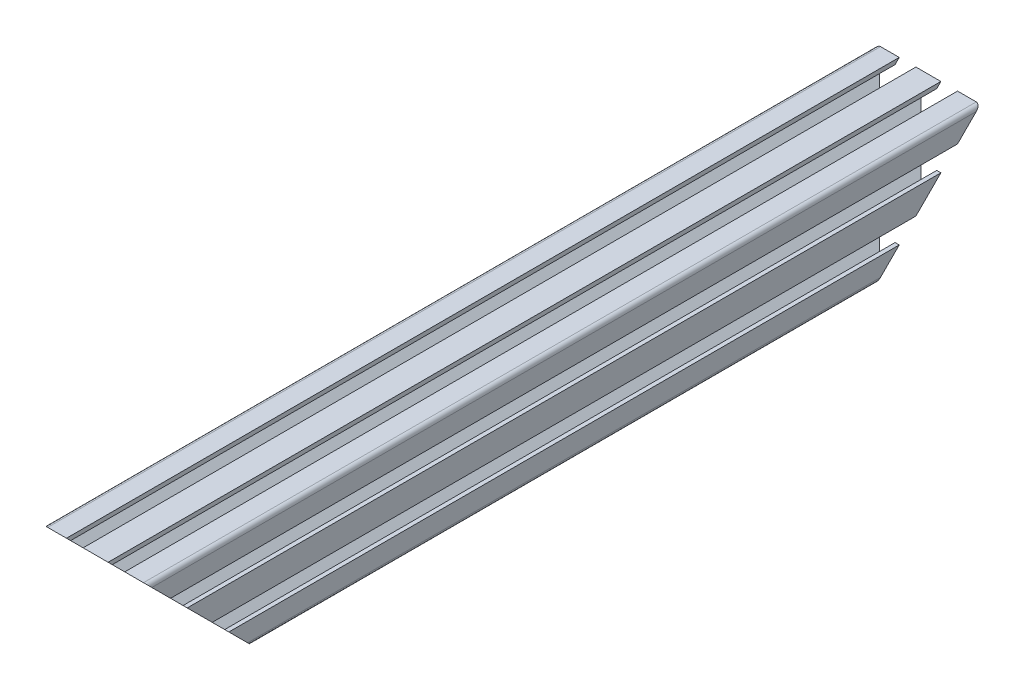
SolidWorks part; units mm, degrees
ref_plane "Front Plane" through (0, 0, 0) normal (0, 0, 1) x (1, 0, 0)
ref_plane "Top Plane" through (0, 0, 0) normal (0, 1, 0) x (1, 0, 0)
ref_plane "Right Plane" through (0, 0, 0) normal (1, 0, 0) x (0, 0, -1)
ref_plane "Plane1" through (0, 0, 0) normal (0, 0, 1) x (1, 0, 0)
sketch "Sketch1" plane through (0, 0, 0) normal (0, 0, 1) x (1, 0, 0)
  line L0 (-25, 23) -> (-25, 14)
  line L1 (-25, 14) -> (-23, 14)
  line L2 (-23, 14) -> (-23, 18.25)
  line L3 (-23, 18.25) -> (-19.6642, 18.25)
  line L4 (-19.6642, 18.25) -> (-16, 14.5858)
  line L5 (-16, 14.5858) -> (-16, 10.6536)
  line L6 (-15.933, 10.4036) -> (-15.7, 10)
  line L7 (-15.7, 10) -> (-15.933, 9.5964)
  line L8 (-15.933, 9.0964) -> (-15.751, 8.7811)
  line L9 (-15.751, 8.7811) -> (-16, 7.5)
  line L10 (-16, 7.5) -> (-16, 5.4142)
  line L11 (-16, 5.4142) -> (-19.6642, 1.75)
  line L12 (-19.6642, 1.75) -> (-23, 1.75)
  line L13 (-23, 1.75) -> (-23, 6)
  line L14 (-23, 6) -> (-25, 6)
  line L15 (-25, 6) -> (-25, -6)
  line L16 (-25, -6) -> (-23, -6)
  line L17 (-23, -6) -> (-23, -1.75)
  line L18 (-23, -1.75) -> (-19.6642, -1.75)
  line L19 (-19.6642, -1.75) -> (-16, -5.4142)
  line L20 (-16, -5.4142) -> (-16, -9.3464)
  line L21 (-15.933, -9.5964) -> (-15.7, -10)
  line L22 (-15.7, -10) -> (-15.933, -10.4036)
  line L23 (-15.933, -10.9036) -> (-15.751, -11.2189)
  line L24 (-15.751, -11.2189) -> (-16, -12.5)
  line L25 (-16, -12.5) -> (-16, -14.5858)
  line L26 (-16, -14.5858) -> (-19.6642, -18.25)
  line L27 (-19.6642, -18.25) -> (-23, -18.25)
  line L28 (-23, -18.25) -> (-23, -14)
  line L29 (-23, -14) -> (-25, -14)
  line L30 (-25, -14) -> (-25, -23)
  line L31 (-23, -25) -> (-14, -25)
  line L32 (-14, -25) -> (-14, -23)
  line L33 (-14, -23) -> (-18.25, -23)
  line L34 (-18.25, -23) -> (-18.25, -19.6642)
  line L35 (-18.25, -19.6642) -> (-14.5858, -16)
  line L36 (-14.5858, -16) -> (-10.6536, -16)
  line L37 (-10.4036, -15.933) -> (-10, -15.7)
  line L38 (-10, -15.7) -> (-9.5964, -15.933)
  line L39 (-9.0964, -15.933) -> (-8.7811, -15.751)
  line L40 (-8.7811, -15.751) -> (-7.5, -16)
  line L41 (-7.5, -16) -> (-5.4142, -16)
  line L42 (-5.4142, -16) -> (-1.75, -19.6642)
  line L43 (-1.75, -19.6642) -> (-1.75, -23)
  line L44 (-1.75, -23) -> (-6, -23)
  line L45 (-6, -23) -> (-6, -25)
  line L46 (-6, -25) -> (6, -25)
  line L47 (6, -25) -> (6, -23)
  line L48 (6, -23) -> (1.75, -23)
  line L49 (1.75, -23) -> (1.75, -19.6642)
  line L50 (1.75, -19.6642) -> (5.4142, -16)
  line L51 (5.4142, -16) -> (9.3464, -16)
  line L52 (9.5964, -15.933) -> (10, -15.7)
  line L53 (10, -15.7) -> (10.4036, -15.933)
  line L54 (10.9036, -15.933) -> (11.2189, -15.751)
  line L55 (11.2189, -15.751) -> (12.5, -16)
  line L56 (12.5, -16) -> (14.5858, -16)
  line L57 (14.5858, -16) -> (18.25, -19.6642)
  line L58 (18.25, -19.6642) -> (18.25, -23)
  line L59 (18.25, -23) -> (14, -23)
  line L60 (14, -23) -> (14, -25)
  line L61 (14, -25) -> (23, -25)
  line L62 (25, -23) -> (25, -14)
  line L63 (25, -14) -> (23, -14)
  line L64 (23, -14) -> (23, -18.25)
  line L65 (23, -18.25) -> (19.6642, -18.25)
  line L66 (19.6642, -18.25) -> (16, -14.5858)
  line L67 (16, -14.5858) -> (16, -10.6536)
  line L68 (15.933, -10.4036) -> (15.7, -10)
  line L69 (15.7, -10) -> (15.933, -9.5964)
  line L70 (15.933, -9.0964) -> (15.751, -8.7811)
  line L71 (15.751, -8.7811) -> (16, -7.5)
  line L72 (16, -7.5) -> (16, -5.4142)
  line L73 (16, -5.4142) -> (19.6642, -1.75)
  line L74 (19.6642, -1.75) -> (23, -1.75)
  line L75 (23, -1.75) -> (23, -6)
  line L76 (23, -6) -> (25, -6)
  line L77 (25, -6) -> (25, 6)
  line L78 (25, 6) -> (23, 6)
  line L79 (23, 6) -> (23, 1.75)
  line L80 (23, 1.75) -> (19.6642, 1.75)
  line L81 (19.6642, 1.75) -> (16, 5.4142)
  line L82 (16, 5.4142) -> (16, 9.3464)
  line L83 (15.933, 9.5964) -> (15.7, 10)
  line L84 (15.7, 10) -> (15.933, 10.4036)
  line L85 (15.933, 10.9036) -> (15.751, 11.2189)
  line L86 (15.751, 11.2189) -> (16, 12.5)
  line L87 (16, 12.5) -> (16, 14.5858)
  line L88 (16, 14.5858) -> (19.6642, 18.25)
  line L89 (19.6642, 18.25) -> (23, 18.25)
  line L90 (23, 18.25) -> (23, 14)
  line L91 (23, 14) -> (25, 14)
  line L92 (25, 14) -> (25, 23)
  line L93 (23, 25) -> (14, 25)
  line L94 (14, 25) -> (14, 23)
  line L95 (14, 23) -> (18.25, 23)
  line L96 (18.25, 23) -> (18.25, 19.6642)
  line L97 (18.25, 19.6642) -> (14.5858, 16)
  line L98 (14.5858, 16) -> (10.6536, 16)
  line L99 (10.4036, 15.933) -> (10, 15.7)
  line L100 (10, 15.7) -> (9.5964, 15.933)
  line L101 (9.0964, 15.933) -> (8.7811, 15.751)
  line L102 (8.7811, 15.751) -> (7.5, 16)
  line L103 (7.5, 16) -> (5.4142, 16)
  line L104 (5.4142, 16) -> (1.75, 19.6642)
  line L105 (1.75, 19.6642) -> (1.75, 23)
  line L106 (1.75, 23) -> (6, 23)
  line L107 (6, 23) -> (6, 25)
  line L108 (6, 25) -> (-6, 25)
  line L109 (-6, 25) -> (-6, 23)
  line L110 (-6, 23) -> (-1.75, 23)
  line L111 (-1.75, 23) -> (-1.75, 19.6642)
  line L112 (-1.75, 19.6642) -> (-5.4142, 16)
  line L113 (-5.4142, 16) -> (-9.3464, 16)
  line L114 (-9.5964, 15.933) -> (-10, 15.7)
  line L115 (-10, 15.7) -> (-10.4036, 15.933)
  line L116 (-10.9036, 15.933) -> (-11.2189, 15.751)
  line L117 (-11.2189, 15.751) -> (-12.5, 16)
  line L118 (-12.5, 16) -> (-14.5858, 16)
  line L119 (-14.5858, 16) -> (-18.25, 19.6642)
  line L120 (-18.25, 19.6642) -> (-18.25, 23)
  line L121 (-18.25, 23) -> (-14, 23)
  line L122 (-14, 23) -> (-14, 25)
  line L123 (-14, 25) -> (-23, 25)
  line L124 (-17.8787, -0.7071) -> (-14.8787, -3.7071)
  line L125 (-14.1716, -4) -> (-10, -4)
  line L126 (-4, -10) -> (-4, -14.1716)
  line L127 (-3.7071, -14.8787) -> (-0.7071, -17.8787)
  line L128 (0.7071, -17.8787) -> (3.7071, -14.8787)
  line L129 (4, -14.1716) -> (4, -10)
  line L130 (10, -4) -> (14.1716, -4)
  line L131 (14.8787, -3.7071) -> (17.8787, -0.7071)
  line L132 (17.8787, 0.7071) -> (14.8787, 3.7071)
  line L133 (14.1716, 4) -> (10, 4)
  line L134 (4, 10) -> (4, 14.1716)
  line L135 (3.7071, 14.8787) -> (0.7071, 17.8787)
  line L136 (-0.7071, 17.8787) -> (-3.7071, 14.8787)
  line L137 (-4, 14.1716) -> (-4, 10)
  line L138 (-10, 4) -> (-14.1716, 4)
  line L139 (-14.8787, 3.7071) -> (-17.8787, 0.7071)
  arc A0 (-16, 10.6536) -> (-15.933, 10.4036) centre (-15.5, 10.6536) ccw
  arc A1 (-15.933, 9.5964) -> (-15.933, 9.0964) centre (-15.5, 9.3464) ccw
  arc A2 (-16, -9.3464) -> (-15.933, -9.5964) centre (-15.5, -9.3464) ccw
  arc A3 (-15.933, -10.4036) -> (-15.933, -10.9036) centre (-15.5, -10.6536) ccw
  arc A4 (-25, -23) -> (-23, -25) centre (-23, -23) ccw
  arc A5 (-10.6536, -16) -> (-10.4036, -15.933) centre (-10.6536, -15.5) ccw
  arc A6 (-9.5964, -15.933) -> (-9.0964, -15.933) centre (-9.3464, -15.5) ccw
  arc A7 (9.3464, -16) -> (9.5964, -15.933) centre (9.3464, -15.5) ccw
  arc A8 (10.4036, -15.933) -> (10.9036, -15.933) centre (10.6536, -15.5) ccw
  arc A9 (23, -25) -> (25, -23) centre (23, -23) ccw
  arc A10 (16, -10.6536) -> (15.933, -10.4036) centre (15.5, -10.6536) ccw
  arc A11 (15.933, -9.5964) -> (15.933, -9.0964) centre (15.5, -9.3464) ccw
  arc A12 (16, 9.3464) -> (15.933, 9.5964) centre (15.5, 9.3464) ccw
  arc A13 (15.933, 10.4036) -> (15.933, 10.9036) centre (15.5, 10.6536) ccw
  arc A14 (25, 23) -> (23, 25) centre (23, 23) ccw
  arc A15 (10.6536, 16) -> (10.4036, 15.933) centre (10.6536, 15.5) ccw
  arc A16 (9.5964, 15.933) -> (9.0964, 15.933) centre (9.3464, 15.5) ccw
  arc A17 (-9.3464, 16) -> (-9.5964, 15.933) centre (-9.3464, 15.5) ccw
  arc A18 (-10.4036, 15.933) -> (-10.9036, 15.933) centre (-10.6536, 15.5) ccw
  arc A19 (-23, 25) -> (-25, 23) centre (-23, 23) ccw
  arc A20 (-17.8787, 0.7071) -> (-17.8787, -0.7071) centre (-17.1716, 0) ccw
  arc A21 (-14.8787, -3.7071) -> (-14.1716, -4) centre (-14.1716, -3) ccw
  arc A22 (-10, -4) -> (-4, -10) centre (-10, -10) cw
  arc A23 (-4, -14.1716) -> (-3.7071, -14.8787) centre (-3, -14.1716) ccw
  arc A24 (-0.7071, -17.8787) -> (0.7071, -17.8787) centre (0, -17.1716) ccw
  arc A25 (3.7071, -14.8787) -> (4, -14.1716) centre (3, -14.1716) ccw
  arc A26 (4, -10) -> (10, -4) centre (10, -10) cw
  arc A27 (14.1716, -4) -> (14.8787, -3.7071) centre (14.1716, -3) ccw
  arc A28 (17.8787, -0.7071) -> (17.8787, 0.7071) centre (17.1716, 0) ccw
  arc A29 (14.8787, 3.7071) -> (14.1716, 4) centre (14.1716, 3) ccw
  arc A30 (10, 4) -> (4, 10) centre (10, 10) cw
  arc A31 (4, 14.1716) -> (3.7071, 14.8787) centre (3, 14.1716) ccw
  arc A32 (0.7071, 17.8787) -> (-0.7071, 17.8787) centre (0, 17.1716) ccw
  arc A33 (-3.7071, 14.8787) -> (-4, 14.1716) centre (-3, 14.1716) ccw
  arc A34 (-4, 10) -> (-10, 4) centre (-10, 10) cw
  arc A35 (-14.1716, 4) -> (-14.8787, 3.7071) centre (-14.1716, 3) ccw
extrude "Boss-Extrude1" add sketch "Sketch1" against normal blind 400
ref_plane "Plane2" through (0, 0, 0) normal (0, 0, 1) x (1, 0, 0)
sketch "Sketch2" plane through (0, 0, 0) normal (0, 0, 1) x (1, 0, 0)
  line L0 (-14.2426, 12.8284) -> (-13.2051, 11.7909)
  line L1 (-13.2051, 8.2091) -> (-14.2426, 7.1716)
  line L2 (-14.2426, 6.4645) -> (-13.5355, 5.7574)
  line L3 (-12.8284, 5.7574) -> (-11.7909, 6.7949)
  line L4 (-6.7949, 11.7909) -> (-5.7574, 12.8284)
  line L5 (-5.7574, 13.5355) -> (-6.4645, 14.2426)
  line L6 (-7.1716, 14.2426) -> (-8.2091, 13.2051)
  line L7 (-11.7909, 13.2051) -> (-12.8284, 14.2426)
  line L8 (-13.5355, 14.2426) -> (-14.2426, 13.5355)
  arc A0 (-14.2426, 13.5355) -> (-14.2426, 12.8284) centre (-13.8891, 13.182) ccw
  arc A1 (-13.2051, 11.7909) -> (-13.1208, 11.3493) centre (-13.4879, 11.508) cw
  arc A2 (-13.1208, 11.3493) -> (-13.1208, 8.6507) centre (-10, 10) ccw
  arc A3 (-13.1208, 8.6507) -> (-13.2051, 8.2091) centre (-13.4879, 8.492) cw
  arc A4 (-14.2426, 7.1716) -> (-14.2426, 6.4645) centre (-13.8891, 6.818) ccw
  arc A5 (-13.5355, 5.7574) -> (-12.8284, 5.7574) centre (-13.182, 6.1109) ccw
  arc A6 (-11.7909, 6.7949) -> (-11.3493, 6.8792) centre (-11.508, 6.5121) cw
  arc A7 (-11.3493, 6.8792) -> (-6.8792, 11.3493) centre (-10, 10) ccw
  arc A8 (-6.8792, 11.3493) -> (-6.7949, 11.7909) centre (-6.5121, 11.508) cw
  arc A9 (-5.7574, 12.8284) -> (-5.7574, 13.5355) centre (-6.1109, 13.182) ccw
  arc A10 (-6.4645, 14.2426) -> (-7.1716, 14.2426) centre (-6.818, 13.8891) ccw
  arc A11 (-8.2091, 13.2051) -> (-8.6507, 13.1208) centre (-8.492, 13.4879) cw
  arc A12 (-8.6507, 13.1208) -> (-11.3493, 13.1208) centre (-10, 10) ccw
  arc A13 (-11.3493, 13.1208) -> (-11.7909, 13.2051) centre (-11.508, 13.4879) cw
  arc A14 (-12.8284, 14.2426) -> (-13.5355, 14.2426) centre (-13.182, 13.8891) ccw
extrude "Cut-Extrude1" cut sketch "Sketch2" against normal through all
ref_plane "Plane3" through (0, 0, 0) normal (0, 0, 1) x (1, 0, 0)
sketch "Sketch3" plane through (0, 0, 0) normal (0, 0, 1) x (1, 0, 0)
  line L0 (-12.8284, -14.2426) -> (-11.7909, -13.2051)
  line L1 (-8.2091, -13.2051) -> (-7.1716, -14.2426)
  line L2 (-6.4645, -14.2426) -> (-5.7574, -13.5355)
  line L3 (-5.7574, -12.8284) -> (-6.7949, -11.7909)
  line L4 (-11.7909, -6.7949) -> (-12.8284, -5.7574)
  line L5 (-13.5355, -5.7574) -> (-14.2426, -6.4645)
  line L6 (-14.2426, -7.1716) -> (-13.2051, -8.2091)
  line L7 (-13.2051, -11.7909) -> (-14.2426, -12.8284)
  line L8 (-14.2426, -13.5355) -> (-13.5355, -14.2426)
  arc A0 (-13.5355, -14.2426) -> (-12.8284, -14.2426) centre (-13.182, -13.8891) ccw
  arc A1 (-11.7909, -13.2051) -> (-11.3493, -13.1208) centre (-11.508, -13.4879) cw
  arc A2 (-11.3493, -13.1208) -> (-8.6507, -13.1208) centre (-10, -10) ccw
  arc A3 (-8.6507, -13.1208) -> (-8.2091, -13.2051) centre (-8.492, -13.4879) cw
  arc A4 (-7.1716, -14.2426) -> (-6.4645, -14.2426) centre (-6.818, -13.8891) ccw
  arc A5 (-5.7574, -13.5355) -> (-5.7574, -12.8284) centre (-6.1109, -13.182) ccw
  arc A6 (-6.7949, -11.7909) -> (-6.8792, -11.3493) centre (-6.5121, -11.508) cw
  arc A7 (-6.8792, -11.3493) -> (-11.3493, -6.8792) centre (-10, -10) ccw
  arc A8 (-11.3493, -6.8792) -> (-11.7909, -6.7949) centre (-11.508, -6.5121) cw
  arc A9 (-12.8284, -5.7574) -> (-13.5355, -5.7574) centre (-13.182, -6.1109) ccw
  arc A10 (-14.2426, -6.4645) -> (-14.2426, -7.1716) centre (-13.8891, -6.818) ccw
  arc A11 (-13.2051, -8.2091) -> (-13.1208, -8.6507) centre (-13.4879, -8.492) cw
  arc A12 (-13.1208, -8.6507) -> (-13.1208, -11.3493) centre (-10, -10) ccw
  arc A13 (-13.1208, -11.3493) -> (-13.2051, -11.7909) centre (-13.4879, -11.508) cw
  arc A14 (-14.2426, -12.8284) -> (-14.2426, -13.5355) centre (-13.8891, -13.182) ccw
extrude "Cut-Extrude2" cut sketch "Sketch3" against normal through all
ref_plane "Plane4" through (0, 0, 0) normal (0, 0, 1) x (1, 0, 0)
sketch "Sketch4" plane through (0, 0, 0) normal (0, 0, 1) x (1, 0, 0)
  line L0 (14.2426, -12.8284) -> (13.2051, -11.7909)
  line L1 (13.2051, -8.2091) -> (14.2426, -7.1716)
  line L2 (14.2426, -6.4645) -> (13.5355, -5.7574)
  line L3 (12.8284, -5.7574) -> (11.7909, -6.7949)
  line L4 (6.7949, -11.7909) -> (5.7574, -12.8284)
  line L5 (5.7574, -13.5355) -> (6.4645, -14.2426)
  line L6 (7.1716, -14.2426) -> (8.2091, -13.2051)
  line L7 (11.7909, -13.2051) -> (12.8284, -14.2426)
  line L8 (13.5355, -14.2426) -> (14.2426, -13.5355)
  arc A0 (14.2426, -13.5355) -> (14.2426, -12.8284) centre (13.8891, -13.182) ccw
  arc A1 (13.2051, -11.7909) -> (13.1208, -11.3493) centre (13.4879, -11.508) cw
  arc A2 (13.1208, -11.3493) -> (13.1208, -8.6507) centre (10, -10) ccw
  arc A3 (13.1208, -8.6507) -> (13.2051, -8.2091) centre (13.4879, -8.492) cw
  arc A4 (14.2426, -7.1716) -> (14.2426, -6.4645) centre (13.8891, -6.818) ccw
  arc A5 (13.5355, -5.7574) -> (12.8284, -5.7574) centre (13.182, -6.1109) ccw
  arc A6 (11.7909, -6.7949) -> (11.3493, -6.8792) centre (11.508, -6.5121) cw
  arc A7 (11.3493, -6.8792) -> (6.8792, -11.3493) centre (10, -10) ccw
  arc A8 (6.8792, -11.3493) -> (6.7949, -11.7909) centre (6.5121, -11.508) cw
  arc A9 (5.7574, -12.8284) -> (5.7574, -13.5355) centre (6.1109, -13.182) ccw
  arc A10 (6.4645, -14.2426) -> (7.1716, -14.2426) centre (6.818, -13.8891) ccw
  arc A11 (8.2091, -13.2051) -> (8.6507, -13.1208) centre (8.492, -13.4879) cw
  arc A12 (8.6507, -13.1208) -> (11.3493, -13.1208) centre (10, -10) ccw
  arc A13 (11.3493, -13.1208) -> (11.7909, -13.2051) centre (11.508, -13.4879) cw
  arc A14 (12.8284, -14.2426) -> (13.5355, -14.2426) centre (13.182, -13.8891) ccw
extrude "Cut-Extrude3" cut sketch "Sketch4" against normal through all
ref_plane "Plane5" through (0, 0, 0) normal (0, 0, 1) x (1, 0, 0)
sketch "Sketch5" plane through (0, 0, 0) normal (0, 0, 1) x (1, 0, 0)
  line L0 (12.8284, 14.2426) -> (11.7909, 13.2051)
  line L1 (8.2091, 13.2051) -> (7.1716, 14.2426)
  line L2 (6.4645, 14.2426) -> (5.7574, 13.5355)
  line L3 (5.7574, 12.8284) -> (6.7949, 11.7909)
  line L4 (11.7909, 6.7949) -> (12.8284, 5.7574)
  line L5 (13.5355, 5.7574) -> (14.2426, 6.4645)
  line L6 (14.2426, 7.1716) -> (13.2051, 8.2091)
  line L7 (13.2051, 11.7909) -> (14.2426, 12.8284)
  line L8 (14.2426, 13.5355) -> (13.5355, 14.2426)
  arc A0 (13.5355, 14.2426) -> (12.8284, 14.2426) centre (13.182, 13.8891) ccw
  arc A1 (11.7909, 13.2051) -> (11.3493, 13.1208) centre (11.508, 13.4879) cw
  arc A2 (11.3493, 13.1208) -> (8.6507, 13.1208) centre (10, 10) ccw
  arc A3 (8.6507, 13.1208) -> (8.2091, 13.2051) centre (8.492, 13.4879) cw
  arc A4 (7.1716, 14.2426) -> (6.4645, 14.2426) centre (6.818, 13.8891) ccw
  arc A5 (5.7574, 13.5355) -> (5.7574, 12.8284) centre (6.1109, 13.182) ccw
  arc A6 (6.7949, 11.7909) -> (6.8792, 11.3493) centre (6.5121, 11.508) cw
  arc A7 (6.8792, 11.3493) -> (11.3493, 6.8792) centre (10, 10) ccw
  arc A8 (11.3493, 6.8792) -> (11.7909, 6.7949) centre (11.508, 6.5121) cw
  arc A9 (12.8284, 5.7574) -> (13.5355, 5.7574) centre (13.182, 6.1109) ccw
  arc A10 (14.2426, 6.4645) -> (14.2426, 7.1716) centre (13.8891, 6.818) ccw
  arc A11 (13.2051, 8.2091) -> (13.1208, 8.6507) centre (13.4879, 8.492) cw
  arc A12 (13.1208, 8.6507) -> (13.1208, 11.3493) centre (10, 10) ccw
  arc A13 (13.1208, 11.3493) -> (13.2051, 11.7909) centre (13.4879, 11.508) cw
  arc A14 (14.2426, 12.8284) -> (14.2426, 13.5355) centre (13.8891, 13.182) ccw
extrude "Cut-Extrude4" cut sketch "Sketch5" against normal through all
sketch "Sketch6" plane through (25, 0, 0) normal (1, 0, 0) x (0, 0, -1)
  line L0 (0, 25) -> (50, -25)
  line L1 (400, -25) -> (0, -25) construction
  line L2 (50, -25) -> (0, -25)
  line L3 (0, -25) -> (0, 25)
  line L4 (400, 25) -> (350, -25)
  line L5 (350, -25) -> (400, -25)
  line L6 (400, -25) -> (400, 25)
  dimension "D1" = 45
  dimension "D2" = 45
extrude "Cut-Extrude5" cut sketch "Sketch6" against normal through all
